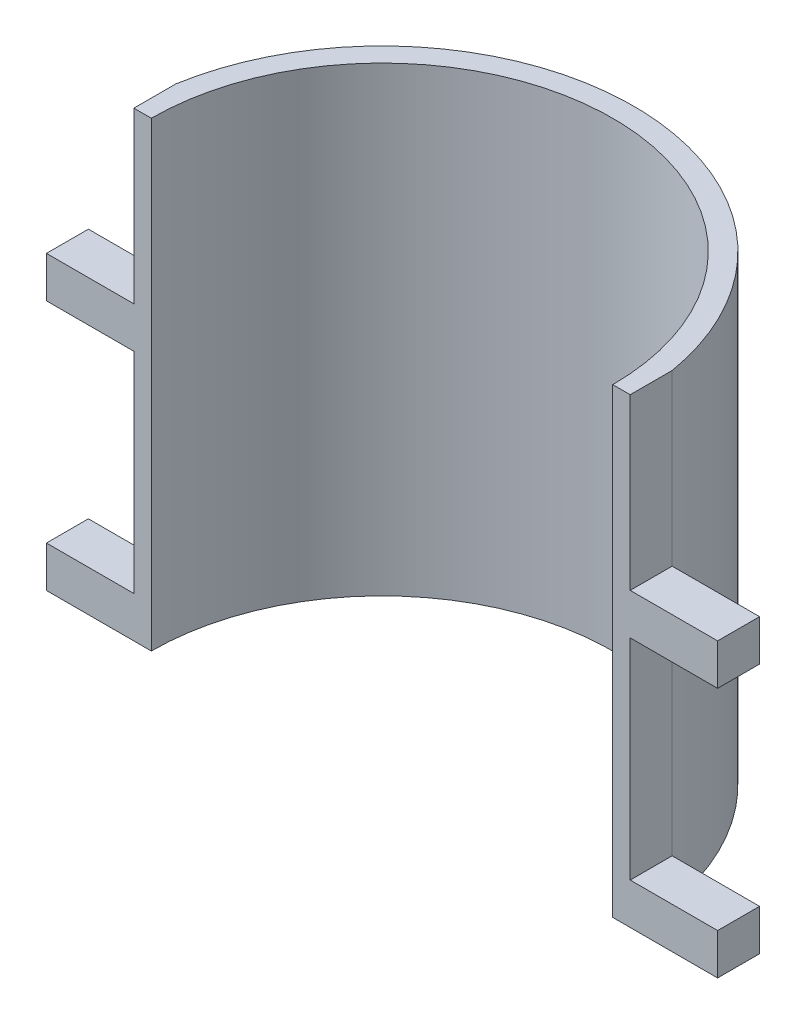
SolidWorks part; units mm, degrees
ref_plane "Front Plane" through (0, 0, 0) normal (0, 0, 1) x (1, 0, 0)
ref_plane "Top Plane" through (0, 0, 0) normal (0, 1, 0) x (1, 0, 0)
ref_plane "Right Plane" through (0, 0, 0) normal (1, 0, 0) x (0, 0, -1)
sketch "Sketch1" plane through (0, 0, 0) normal (0, 1, 0) x (1, 0, 0)
  line L0 (103.6385, 0) -> (-103.6385, 0)
  line L1 (0, -55) -> (0, 55) construction
  line L2 (55, 10) -> (80, 10)
  line L3 (55, 10) -> (55, 0)
  line L4 (55, 0) -> (80, 0)
  line L5 (80, 10) -> (80, 0)
  line L6 (-55, 0) -> (-80, 0)
  line L7 (-80, 10) -> (-80, 0)
  line L8 (-55, 10) -> (-80, 10)
  line L9 (-55, 10) -> (-55, 0)
  circle A0 centre (0, 0) radius 55
  arc A1 (-60, 0) -> (60, 0) centre (0, 0) cw
  point P6 (0, 0)
  dimension "D1" = 110
  dimension "D2" = 207.2771
  dimension "D3" = 60
  dimension "D4" = 25
  dimension "D5" = 10
extrude "Boss-Extrude1" add sketch "Sketch1" along normal blind 110 contours A1 L8 L9 A0 L3 L2 | A1 L0 L9 L8 | L6 A1 L8 L7 | L2 A1 L0 L5 | A1 L2 L3 L4
sketch "Sketch3" plane through (0, 0, -10) normal (0, 0, -1) x (-1, 0, 0)
  line L1 (-80, 59.8) -> (80, 59.8)
  line L2 (-80, 59.8) -> (-80, 9.8)
  line L3 (-80, 9.8) -> (80, 9.8)
  line L4 (80, 59.8) -> (80, 9.8)
  line L5 (80, 110) -> (80, 0) construction
  line L7 (-59.1608, 110) -> (-59.1608, 0) construction
  line L8 (-80, 69.6) -> (80, 69.6)
  line L9 (-80, 69.6) -> (-80, 0)
  line L10 (-80, 0) -> (80, 0)
  line L11 (80, 69.6) -> (80, 0)
  line L12 (-59.1608, 69.6) -> (59.1608, 69.6)
  line L13 (-59.1608, 69.6) -> (-59.1608, 0)
  line L14 (-59.1608, 0) -> (59.1608, 0)
  line L15 (59.1608, 69.6) -> (59.1608, 0)
  line L16 (-80, 110) -> (-80, 0) construction
  line L17 (-80, 110) -> (-59.1608, 110)
  line L18 (-80, 110) -> (-80, 69.6)
  line L19 (-80, 69.6) -> (-59.1608, 69.6)
  line L20 (-59.1608, 110) -> (-59.1608, 69.6)
  line L21 (59.1608, 110) -> (80, 110)
  line L22 (59.1608, 110) -> (59.1608, 69.6)
  line L23 (59.1608, 69.6) -> (80, 69.6)
  line L24 (80, 110) -> (80, 69.6)
  line L25 (59.1608, 0) -> (80, 0) construction
  line L26 (59.1608, 110) -> (80, 110) construction
  point P4 (-75, 70)
  point P5 (-80, 60)
  point P25 (-75, 60)
  point P31 (54.0833, 110)
  point P32 (54.0833, 117.05)
  point P33 (0, 0)
  point P34 (75, 110)
  point P37 (0, 0)
  point P38 (0, 0)
  point P39 (59.1608, 0)
  point P41 (0, 0)
  point P42 (80, 0)
  point P44 (0, 0)
  point P45 (0, 0)
  point P46 (0, 0)
  point P47 (-80, 110)
  line M9 (59.1608, 110) -> (59.1608, 0)
  line M11 (80, 0) -> (80, 110)
  dimension "D1" = 9.8
  dimension "D2" = 50
  dimension "D3" = 9.8
extrude "Cut-Extrude1" cut sketch "Sketch3" against normal blind 110 contours L13 L1 L2 L3 | L3 L1 M9 M11 | L18 L17 L20 L19 | L22 L21 L24 L23
